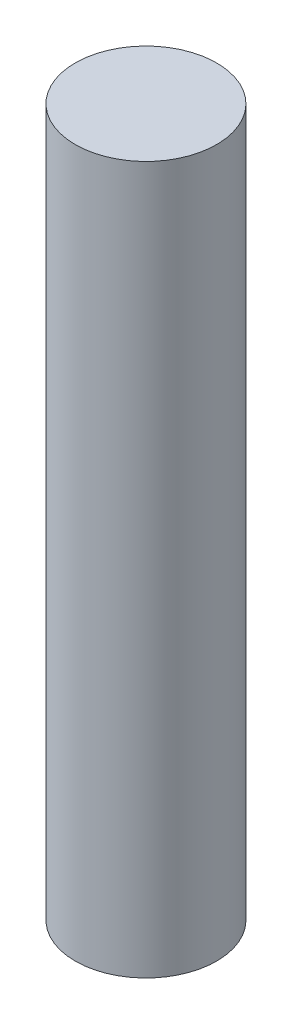
SolidWorks part; units mm, degrees
material "AISI 304"
ref_plane "前视基准面" through (0, 0, 0) normal (0, 0, 1) x (1, 0, 0)
ref_plane "上视基准面" through (0, 0, 0) normal (0, 1, 0) x (1, 0, 0)
ref_plane "右视基准面" through (0, 0, 0) normal (1, 0, 0) x (0, 0, -1)
sketch "Sketch1" plane through (0, 0, 0) normal (0, 1, 0) x (1, 0, 0)
  circle A0 centre (0, 0) radius 5
  dimension "D1" = 10
extrude "Boss-Extrude1" add sketch "Sketch1" along normal blind 50
